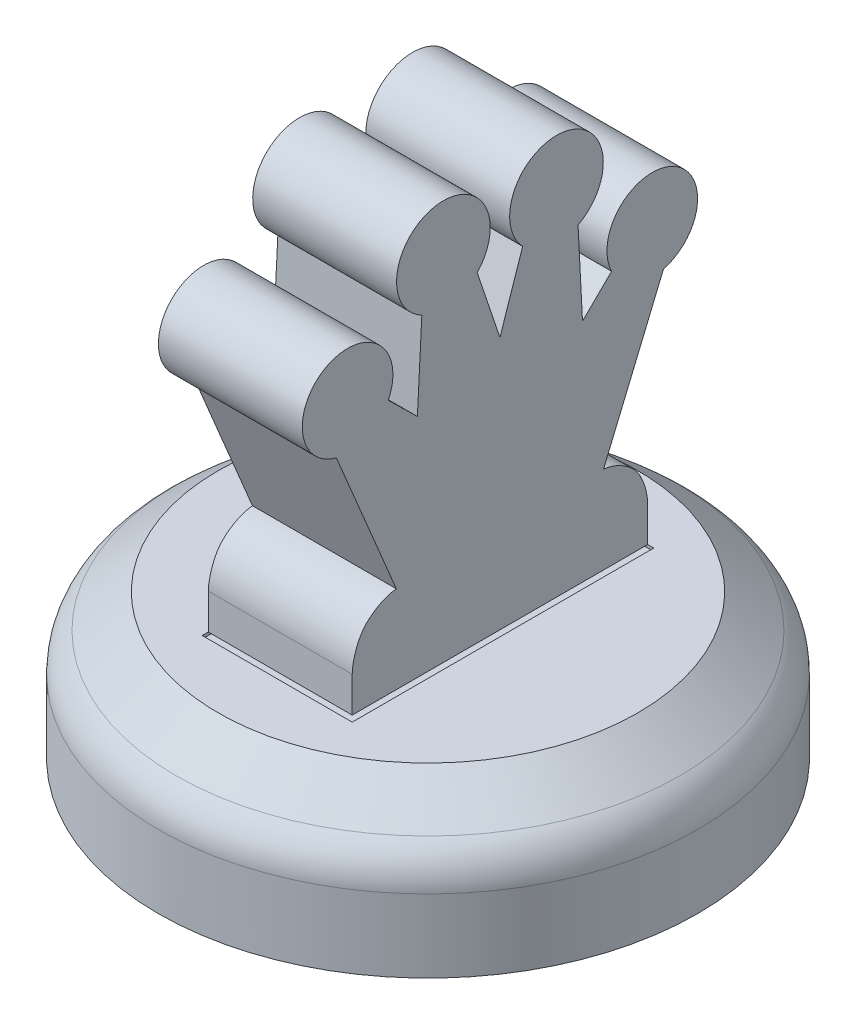
SolidWorks part; units mm, degrees
ref_plane "Front" through (0, 0, 0) normal (0, 0, 1) x (1, 0, 0)
ref_plane "Top" through (0, 0, 0) normal (0, 1, 0) x (1, 0, 0)
ref_plane "Right" through (0, 0, 0) normal (1, 0, 0) x (0, 0, -1)
sketch "Sketch1" plane through (0, 0, 0) normal (0, 1, 0) x (1, 0, 0)
  circle A0 centre (0, 0) radius 17.8594
  dimension "D1" = 35.7188
extrude "Boss-Extrude1" add sketch "Sketch1" along normal blind 6.35
sketch "Sketch2" plane through (0, 0, 0) normal (0, 0, 1) x (1, 0, 0)
  line L0 (-17.8594, 6.35) -> (-13.8906, 9.525)
  line L1 (-13.8906, 9.525) -> (0, 9.525)
  line L2 (0, 9.525) -> (0, 6.35)
  line L3 (17.8594, 6.35) -> (-17.8594, 6.35) construction
  line L4 (0, 6.35) -> (-17.8594, 6.35)
  line L5 (-17.8594, 0) -> (17.8594, 0) construction
  dimension "D1" = 3.9688
  dimension "D2" = 9.525
revolve "Revolve1" add sketch "Sketch2" angle 360 about L2
sketch "Sketch3" plane through (0, 0, 0) normal (0, -1, 0) x (1, 0, 0)
  line L1 (-6.4516, -9.6266) -> (6.4516, -9.6266)
  line L2 (-6.4516, -9.6266) -> (-6.4516, 9.6266)
  line L3 (-6.4516, 9.6266) -> (6.4516, 9.6266)
  line L4 (6.4516, -9.6266) -> (6.4516, 9.6266)
  line L5 (-6.4516, -9.6266) -> (6.4516, 9.6266) construction
  line L6 (-6.4516, 9.6266) -> (6.4516, -9.6266) construction
  point P0 (0, 0)
  dimension "D1" = 19.2532
  dimension "D2" = 12.9032
extrude "Cut-Extrude1" cut sketch "Sketch3" against normal blind 4.7625
hole_wizard "#6 (0.204) Diameter Hole1" positions "Sketch4" profile "Sketch5" hole size "#6" standard "ANSI Inch" end condition through all
sketch "Sketch4" plane through (0, 4.7625, 0) normal (0, -1, 0) x (-1, 0, 0)
  point P0 (0, 0)
sketch "Sketch5" plane through (0, 4.7625, 0) normal (1, 0, 0) x (0, 0, -1)
  line L0 (0, 0) -> (0, 4.7625)
  line L1 (0, 4.7625) -> (2.5908, 4.7625)
  line L2 (2.5908, 4.7625) -> (2.5908, 0)
  line L5 (2.5908, 0) -> (0, 0)
  line L11 (0, -6.35) -> (0, 107.95) construction
  dimension "Thru Hole Dia." = 5.1816
  dimension "Thru Hole Depth" = 4.7625
sketch "Sketch6" plane through (0, 0, 0) normal (1, 0, 0) x (0, 0, -1)
  line L0 (26.0368, 134.5532) -> (196.7034, 134.5532) construction
  line L1 (-9.779, 9.525) -> (9.779, 9.525)
  line L2 (13.8906, 9.525) -> (-13.8906, 9.525) construction
  line L3 (-9.779, 9.525) -> (-9.779, 12.065)
  line L4 (9.779, 9.525) -> (9.779, 12.065)
  line L5 (-6.8573, 15.5044) -> (-10.8288, 24.9967)
  line L6 (-12.3427, 27.9032) -> (-7.9537, 27.9032) construction
  line L7 (-10.0856, 30.1221) -> (-10.0856, 27.9032) construction
  line L8 (-7.3917, 26.583) -> (-5.4654, 24.6892)
  line L9 (-5.4654, 24.6892) -> (-5.1703, 30.3496)
  line L10 (-6.1414, 33.1017) -> (-1.478, 33.1017) construction
  line L11 (-3.7425, 35.4258) -> (-3.7425, 33.1017) construction
  line L12 (-1.505, 30.9556) -> (0, 26.482)
  line L13 (0, 50) -> (0, -50) construction
  line L14 (6.8573, 15.5044) -> (10.8288, 24.9967)
  line L15 (7.3917, 26.583) -> (5.4654, 24.6892)
  line L16 (5.4654, 24.6892) -> (5.1703, 30.3496)
  line L17 (1.505, 30.9556) -> (0, 26.482)
  arc A0 (-10.8288, 24.9967) -> (-7.3917, 26.583) centre (-10.0856, 27.9032) cw
  arc A1 (-5.1703, 30.3496) -> (-1.505, 30.9556) centre (-3.7425, 33.1017) cw
  arc A2 (10.8288, 24.9967) -> (7.3917, 26.583) centre (10.0856, 27.9032) ccw
  arc A3 (5.1703, 30.3496) -> (1.505, 30.9556) centre (3.7425, 33.1017) ccw
  spline S0 degree 3 poles (-9.779, 12.065) (-9.779, 12.3095) (-9.7012, 12.8452) (-9.4535, 13.612) (-9.038, 14.3662) (-8.4052, 14.9249) (-7.6672, 15.338) (-7.1293, 15.4763) (-6.8573, 15.5044) knots 0 0 0 0 0.148073 0.327673 0.488762 0.665615 0.833549 1 1 1 1
  spline S1 degree 3 poles (9.779, 12.065) (9.779, 12.3095) (9.7012, 12.8452) (9.4535, 13.612) (9.038, 14.3662) (8.4052, 14.9249) (7.6672, 15.338) (7.1293, 15.4763) (6.8573, 15.5044) knots 0 0 0 0 0.148073 0.327673 0.488762 0.665615 0.833549 1 1 1 1
  point P6 (0, 9.525)
  dimension "D1" = 19.558
  dimension "D2" = 2.54
extrude "Boss-Extrude2" add sketch "Sketch6" along normal mid plane 9.525 separate body
sketch "Sketch7" plane through (0, 9.525, 0) normal (0, 1, 0) x (1, 0, 0)
  line L14 (4.9657, 9.9822) -> (-4.9657, 9.9822)
  line L15 (-4.9657, 9.9822) -> (-4.9657, -9.9822)
  line L16 (-4.9657, -9.9822) -> (4.9657, -9.9822)
  line L17 (4.9657, -9.9822) -> (4.9657, 9.9822)
  line L18 (4.9657, 9.9822) -> (-4.9657, 9.9822)
  line L19 (-4.9657, 9.9822) -> (-4.9657, -9.9822)
  line L20 (-4.9657, -9.9822) -> (4.9657, -9.9822)
  line L21 (4.9657, -9.9822) -> (4.9657, 9.9822)
  dimension "D1" = 0.2032
extrude "Cut-Extrude2" cut sketch "Sketch7" against normal mid plane 0.3969
fillet "Fillet1" radius 3.175 1 edges at (0, 6.35, 17.8594)
